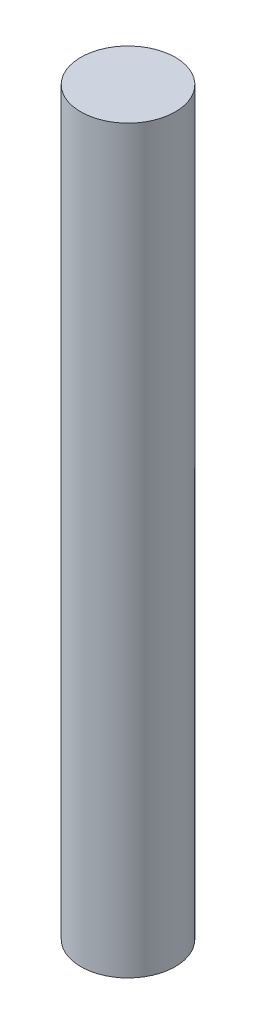
SolidWorks part; units mm, degrees
ref_plane "Front Plane" through (0, 0, 0) normal (0, 0, 1) x (1, 0, 0)
ref_plane "Top Plane" through (0, 0, 0) normal (0, 1, 0) x (1, 0, 0)
ref_plane "Right Plane" through (0, 0, 0) normal (1, 0, 0) x (0, 0, -1)
sketch "Sketch1" plane through (0, 0, 0) normal (0, 1, 0) x (1, 0, 0)
  circle A0 centre (0, 0) radius 0.8
  dimension "D1" = 1.6
extrude "Boss-Extrude1" add sketch "Sketch1" along normal blind 12.53
